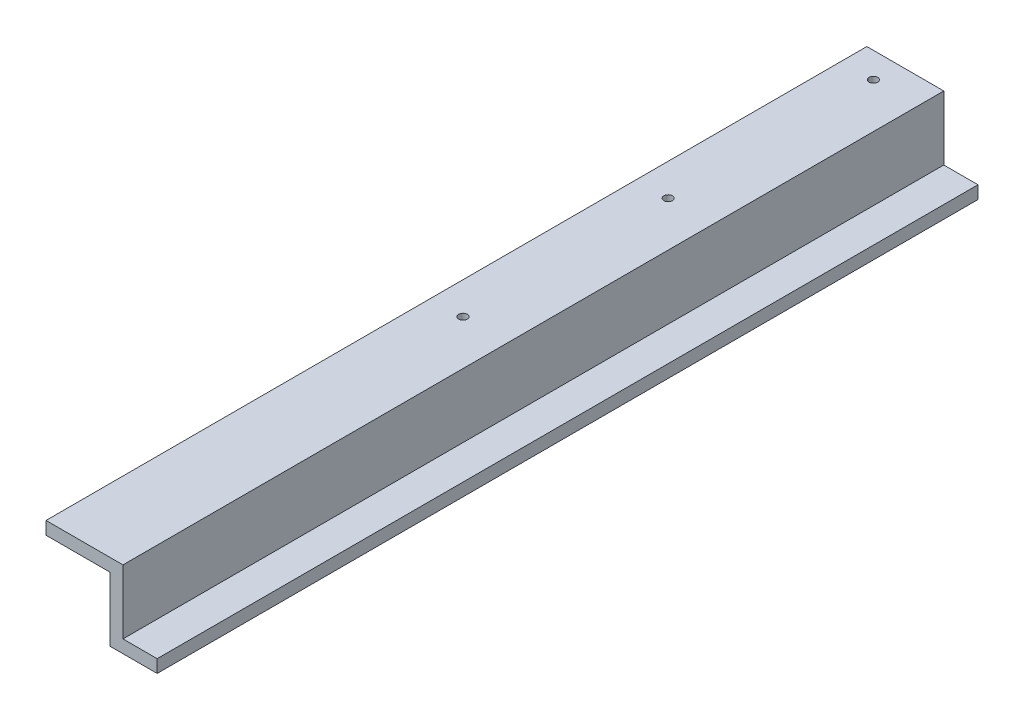
SolidWorks part; units mm, degrees
ref_plane "Front Plane" through (0, 0, 0) normal (0, 0, 1) x (1, 0, 0)
ref_plane "Top Plane" through (0, 0, 0) normal (0, 1, 0) x (1, 0, 0)
ref_plane "Right Plane" through (0, 0, 0) normal (1, 0, 0) x (0, 0, -1)
sketch "Sketch1" plane through (0, 0, 0) normal (0, 0, 1) x (1, 0, 0)
  line L0 (0, -11.9062) -> (0, 11.9062) construction
  line L1 (0, 11.9062) -> (-26.1938, 11.9062) construction
  line L2 (0, -11.9062) -> (26.1938, -11.9062) construction
  line L3 (2.3812, -9.525) -> (26.1938, -9.525) construction
  line L4 (2.3812, -9.525) -> (2.3812, 14.2875) construction
  line L5 (2.3812, 14.2875) -> (-26.1938, 14.2875) construction
  line L6 (-2.3812, -14.2875) -> (26.1938, -14.2875) construction
  line L7 (-2.3812, -14.2875) -> (-2.3812, 9.525) construction
  line L8 (-2.3812, 9.525) -> (-26.1938, 9.525) construction
  line L9 (-26.1938, 14.2875) -> (-26.1938, 9.525) construction
  line L10 (26.1938, -9.525) -> (26.1938, -14.2875) construction
  point P4 (0, 0)
  dimension "Leg Width" = 28.575
  dimension "Outside Height" = 28.575
  dimension "Wall Thickness" = 4.7625
sketch "Sketch2" plane through (0, 0, 0) normal (1, 0, 0) x (0, 0, -1)
  line L0 (152.4, 0) -> (-152.4, 0) construction
  line L1 (0, 0) -> (0, 14.2875) construction
  line L2 (-152.4, 0) -> (-152.4, 14.2875) construction
  line L3 (152.4, 0) -> (152.4, 14.2875) construction
  point P0 (-114.3, 0)
  point P3 (114.3, 0)
  point P4 (0, 0)
  dimension "D1" = 228.6
  dimension "Length" = 304.8
sketch "Sketch3" plane through (0, 0, 0) normal (0, 0, 1) x (1, 0, 0)
  line L1 (2.3812, -9.525) -> (26.1938, -9.525) construction
  line L2 (-2.3812, -14.2875) -> (26.1938, -14.2875) construction
  line L3 (-2.3812, -14.2875) -> (-2.3812, 9.525) construction
  line L4 (2.3812, -9.525) -> (2.3812, 14.2875) construction
  line L5 (2.3812, 14.2875) -> (-26.1938, 14.2875) construction
  line L6 (-26.1938, 14.2875) -> (-26.1938, 9.525) construction
  line L7 (-2.3812, 9.525) -> (-26.1938, 9.525) construction
  line L8 (15.0812, -9.525) -> (15.0812, -14.2875)
  line L9 (2.3812, -9.525) -> (15.0812, -9.525)
  line L10 (-2.3812, -14.2875) -> (15.0812, -14.2875)
  line L11 (-2.3812, -14.2875) -> (-2.3812, 9.525)
  line L12 (2.3812, -9.525) -> (2.3812, 14.2875)
  line L13 (2.3812, 14.2875) -> (-26.1938, 14.2875)
  line L14 (-26.1938, 14.2875) -> (-26.1938, 9.525)
  line L15 (-2.3812, 9.525) -> (-26.1938, 9.525)
extrude "Boss-Extrude1" add sketch "Sketch3" along normal up to vertex (152.4 mm away) and the other way up to vertex (152.4 mm away) up to point (0, 0, 152.4) other way up to point (0, 0, -152.4)
sketch "Sketch6" plane through (0, 9.525, 0) normal (0, -1, 0) x (1, 0, 0)
  circle A3 centre (-14.2875, 9.4639) radius 1.5875
  circle A4 centre (-14.2875, -66.7361) radius 1.5875
  circle A5 centre (-14.2875, -142.9361) radius 1.5875
  point P2 (0, 0)
  dimension "D1" = 76.2
  dimension "D2" = 76.2
extrude "Cut-Extrude1" cut sketch "Sketch6" against normal blind 4.7625 contours A3 | A4 | A5
equation "\"D1@Sketch2\"=\"Length@Sketch2\"*0.75"
